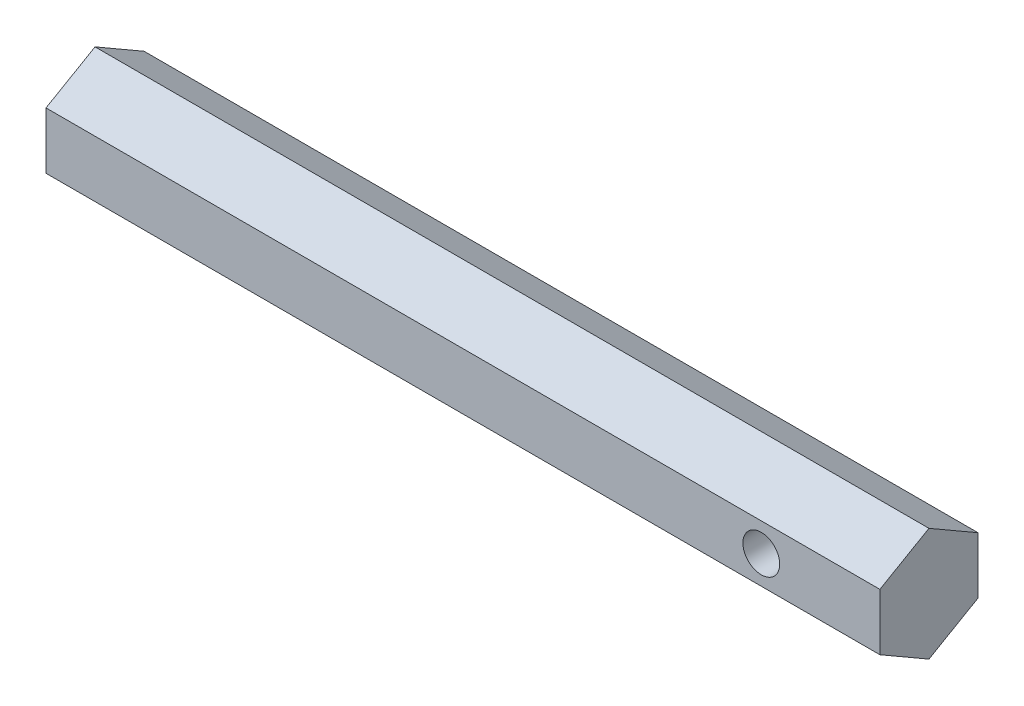
SolidWorks part; units mm, degrees
ref_plane "Front" through (0, 0, 0) normal (0, 0, 1) x (1, 0, 0)
ref_plane "Top" through (0, 0, 0) normal (0, 1, 0) x (1, 0, 0)
ref_plane "Right" through (0, 0, 0) normal (1, 0, 0) x (0, 0, -1)
sketch "Sketch1" plane through (0, 0, 0) normal (1, 0, 0) x (0, 0, -1)
  line L1 (6.35, -3.6662) -> (6.35, 3.6662)
  line L2 (6.35, 3.6662) -> (0, 7.3323)
  line L3 (0, 7.3323) -> (-6.35, 3.6662)
  line L4 (-6.35, 3.6662) -> (-6.35, -3.6662)
  line L5 (-6.35, -3.6662) -> (0, -7.3323)
  line L6 (0, -7.3323) -> (6.35, -3.6662)
  circle A0 centre (0, 0) radius 6.35 construction
  dimension "D1" = 12.7
extrude "Boss-Extrude1" add sketch "Sketch1" along normal blind 107.95
sketch "Sketch2" plane through (0, 0, 6.35) normal (0, 0, 1) x (1, 0, 0)
  line L0 (0, 3.6662) -> (0, -3.6662) construction
  circle A0 centre (92.5968, 0) radius 2.3813
  dimension "D2" = 4.7625
  dimension "D1" = 92.5968
extrude "Cut-Extrude1" cut sketch "Sketch2" against normal through all
